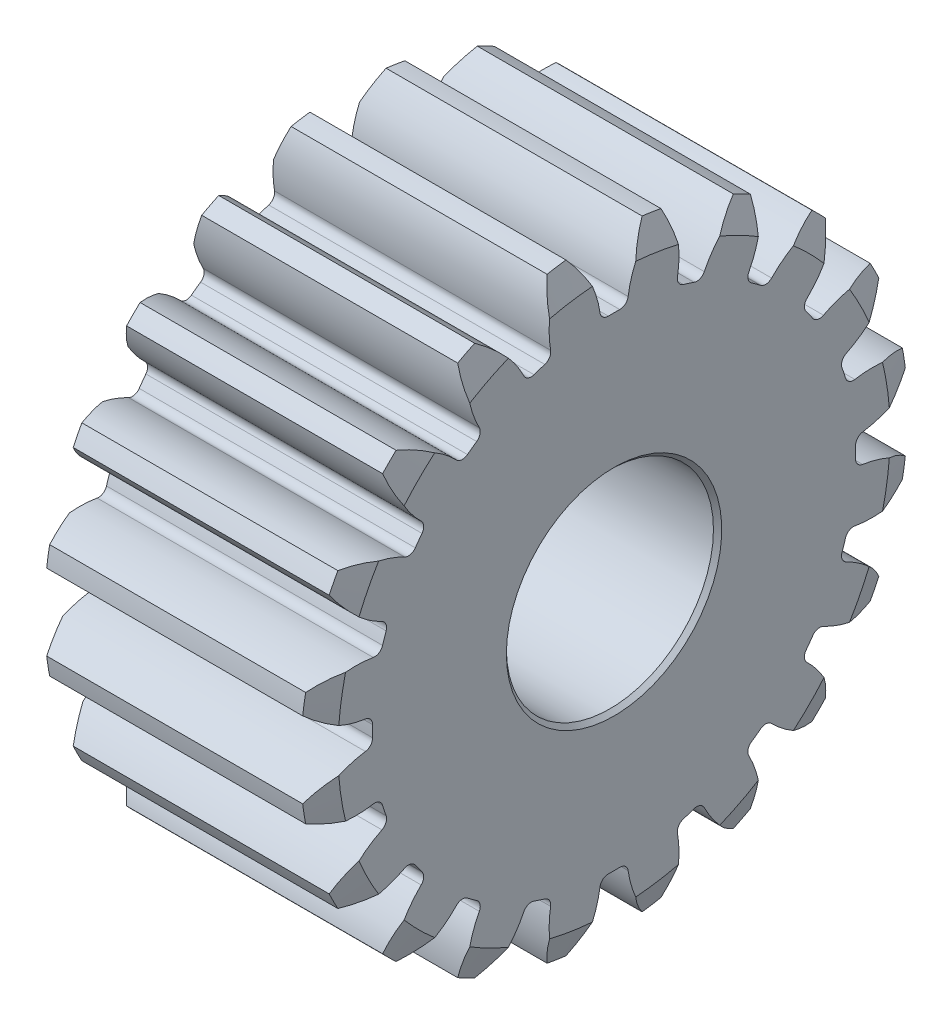
SolidWorks part; units mm, degrees
ref_plane "前视基准面" through (0, 0, 0) normal (0, 0, 1) x (1, 0, 0)
ref_plane "上视基准面" through (0, 0, 0) normal (0, 1, 0) x (1, 0, 0)
ref_plane "右视基准面" through (0, 0, 0) normal (1, 0, 0) x (0, 0, -1)
sketch "草图1" plane through (0, 0, 0) normal (0, 0, 1) x (1, 0, 0)
  line L1 (0, 0) -> (20, 0)
  line L2 (0, 0) -> (0, 22)
  line L3 (0, 22) -> (20, 22)
  line L4 (20, 0) -> (20, 22)
  dimension "D1" = 22
  dimension "D2" = 20
revolve "旋转1" add sketch "草图1" angle 360 about L1
sketch "草图21" plane through (0, 0, 0) normal (-1, 0, 0) x (0, 0, 1)
  line L0 (0, 0) -> (22, 0) construction
  line L1 (0, 0) -> (21.8265, 2.7573) construction
  line L2 (0, 0) -> (19.9383, 1.5692) construction
  line L3 (0, 0) -> (17.4736, 0.9616) construction
  circle A0 centre (0, 0) radius 20 construction
  arc A1 (17.4736, -0.9616) -> (17.4736, 0.9616) centre (0, 0) ccw
  arc A2 (21.8265, -2.7573) -> (21.8265, 2.7573) centre (0, 0) ccw
  arc A3 (17.4736, 0.9616) -> (21.8265, 2.7573) centre (16.9405, 8.4277) ccw
  arc A4 (17.4736, -0.9616) -> (21.8265, -2.7573) centre (16.9405, -8.4277) cw
  dimension "D1" = 40
  dimension "D2" = 35
  dimension "D3" = 44
  dimension "D4" = 3.15
  dimension "D5" = 4.5
  dimension "D6" = 7.2
extrude "切除-拉伸15" cut sketch "草图21" against normal through all
fillet "圆角1" radius 0.6 2 edges at (10, -0.9616, 17.4736) (10, 0.9616, 17.4736)
pattern_circular "阵列(圆周)1" count 20 over 360 about axis through (0, 0, 0) along (1, 0, 0) of "切除-拉伸15", "圆角1"
sketch "草图14" [suppressed] plane through (0, 0, 0) normal (0, 0, 1) x (1, 0, 0)
  line L0 (15, -19.5) -> (15, 19.5) construction
  line L1 (15, 0) -> (27, 0)
  line L2 (15, 0) -> (15, 15)
  line L3 (15, 15) -> (27, 15)
  line L4 (27, 0) -> (27, 15)
  dimension "D1" = 16
  dimension "D2" = 36
revolve "旋转3" [suppressed] add sketch "草图14" angle 360 about L1
sketch "草图5" plane through (0, 0, 0) normal (-1, 0, 0) x (0, 0, 1)
  circle A0 centre (0, 0) radius 7.5
  dimension "D1" = 15
extrude "切除-拉伸3" cut sketch "草图5" against normal through all
chamfer "倒角1" distance 0.3 angle 45 2 edges at (20, 0, 7.5) (0, 0, 7.5)
sketch "草图15" [suppressed] plane through (0, 0, 0) normal (0, 1, 0) x (1, 0, 0)
  line L0 (27, -15) -> (27, 15) construction
  circle A0 centre (23, 0) radius 1.72
  dimension "D1" = 4.3
  dimension "D2" = 5
extrude "切除-拉伸11" [suppressed] cut sketch "草图15" along normal through all
cosmetic thread "装饰螺纹线5" [suppressed] parameters "D2"=5
sketch "草图16" [suppressed] plane through (0, 0, 0) normal (-1, 0, 0) x (0, 0, 1)
  line L0 (0, 0) -> (0, 9.8869) construction
  line L1 (-1.5, 11.4) -> (1.5, 11.4)
  line L2 (-1.5, 11.4) -> (-1.5, 9.8869)
  line L3 (-1.5, 9.8869) -> (1.5, 9.8869)
  line L4 (1.5, 11.4) -> (1.5, 9.8869)
  line L5 (0, 0) -> (1.5, 9.8869) construction
  dimension "D1" = 8.9
  dimension "D2" = 3
  dimension "D3" = 7.5
extrude "切除-拉伸12" [suppressed] cut sketch "草图16" against normal through all
sketch "草图20" plane through (0, 0, 0) normal (0, 0, 1) x (1, 0, 0)
  line L0 (0, 20) -> (0, 22)
  line L1 (0, 22) -> (0.7279, 22)
  line L2 (0.7279, 22) -> (0, 20)
  line L3 (10, 21.2744) -> (10, 13.1591) construction
  line L4 (19.2721, 22) -> (20, 20)
  line L5 (20, 22) -> (19.2721, 22)
  line L6 (20, 20) -> (20, 22)
  line L7 (-1000, 0) -> (49000, 0) construction
  dimension "D1" = 20
  dimension "D2" = 22
  dimension "D3" = 20
  dimension "D4" = 10
revolve "切除-旋转1" cut sketch "草图20" angle 360 about L7
sketch "草图17" [suppressed] plane through (0, 0, 0) normal (0, 0, 1) x (1, 0, 0)
  line L0 (27, -35) -> (27, 35) construction
  circle A0 centre (23, 0) radius 2.58
  dimension "D1" = 4.3
  dimension "D2" = 5
extrude "切除-拉伸13" [suppressed] cut sketch "草图17" along normal through all
cosmetic thread "装饰螺纹线6" [suppressed] parameters "D2"=5
sketch "草图18" [suppressed] plane through (0, 0, 0) normal (0, 0, 1) x (1, 0, 0)
  line L0 (0, 0) -> (20, 0) construction
  line L1 (20, -8) -> (20, 8) construction
ref_plane "基准面1" [suppressed] through (0, 0, 0) normal (0, 0.866, -0.5) x (1, 0, 0)
sketch "草图19" [suppressed] plane through (0, 0, 0) normal (0, 0.866, -0.5) x (1, 0, 0)
  line L0 (20, -8) -> (20, 8) construction
  circle A0 centre (16, 0) radius 1.72
  dimension "D2" = 4.3
  dimension "D1" = 5
extrude "切除-拉伸14" [suppressed] cut sketch "草图19" against normal through all
cosmetic thread "装饰螺纹线7" [suppressed] parameters "D2"=5
